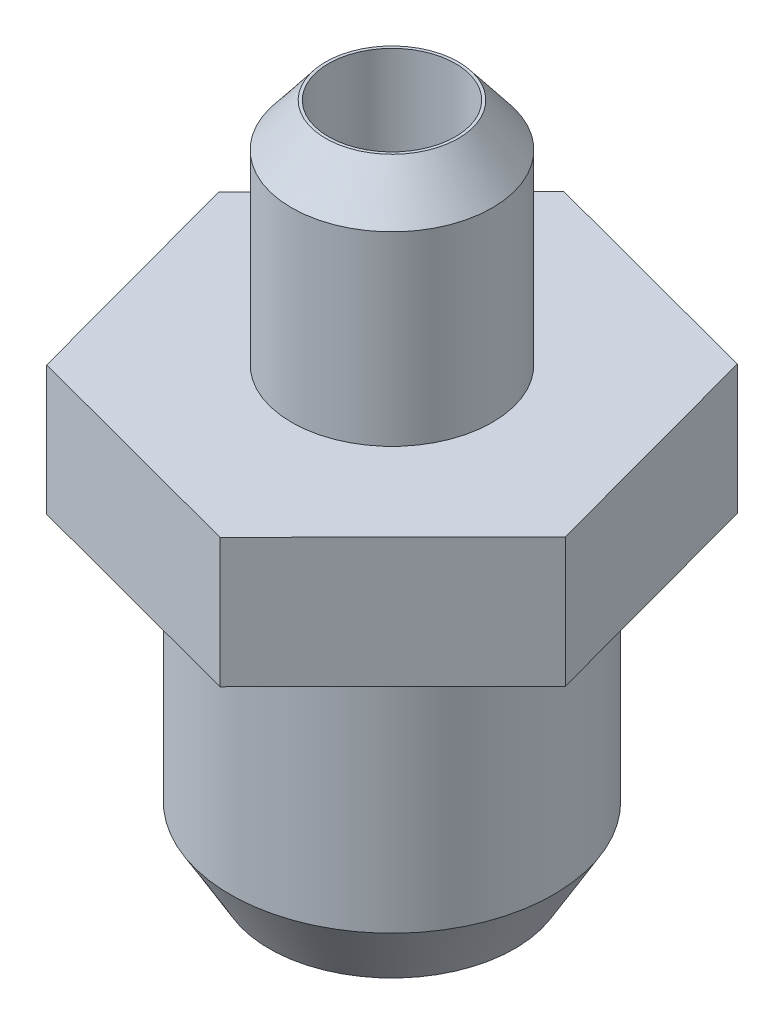
SolidWorks part; units mm, degrees
ref_plane "Front Plane" through (0, 0, 0) normal (0, 0, 1) x (1, 0, 0)
ref_plane "Top Plane" through (0, 0, 0) normal (0, 1, 0) x (1, 0, 0)
ref_plane "Right Plane" through (0, 0, 0) normal (1, 0, 0) x (0, 0, -1)
sketch "Sketch1" plane through (0, 0, 0) normal (0, 0, 1) x (1, 0, 0)
  line L0 (0, 0) -> (0, 40.6)
  line L1 (0, 0) -> (7.4, 0)
  line L4 (7.4, 0) -> (9.75, 4)
  line L5 (9.75, 4) -> (9.75, 19)
  line L6 (9.75, 19) -> (12.7, 19)
  line L7 (12.7, 19) -> (12.7, 26.8)
  line L9 (6.05, 26.8) -> (6.05, 38)
  line L10 (0, 40.6) -> (4, 40.6)
  line L11 (6.05, 38) -> (4, 40.6)
  line L12 (12.7, 26.8) -> (6.05, 26.8)
revolve "Revolve1" add sketch "Sketch1" angle 360 about L0
sketch "Sketch2" plane through (0, 40.6, 0) normal (0, 1, 0) x (1, 0, 0)
  circle A0 centre (0, 0) radius 4
sketch "Sketch3" plane through (0, 26.8, 0) normal (0, 1, 0) x (1, 0, 0)
  line L1 (14.2247, -3.7776) -> (10.3838, 10.4301)
  line L2 (10.3838, 10.4301) -> (-3.8408, 14.2077)
  line L3 (-3.8408, 14.2077) -> (-14.2247, 3.7776)
  line L4 (-14.2247, 3.7776) -> (-10.3838, -10.4301)
  line L5 (-10.3838, -10.4301) -> (3.8408, -14.2077)
  line L6 (3.8408, -14.2077) -> (14.2247, -3.7776)
  circle A0 centre (0, 0) radius 12.7459 construction
extrude "Boss-Extrude1" add sketch "Sketch3" against normal up to surface (7.8 mm away) up to face at (0, 19, -12.7)
sketch "Sketch4" plane through (0, 40.6, 0) normal (0, 1, 0) x (1, 0, 0)
  circle A0 centre (0, 0) radius 3.8254
extrude "Cut-Extrude2" cut sketch "Sketch4" against normal through all
